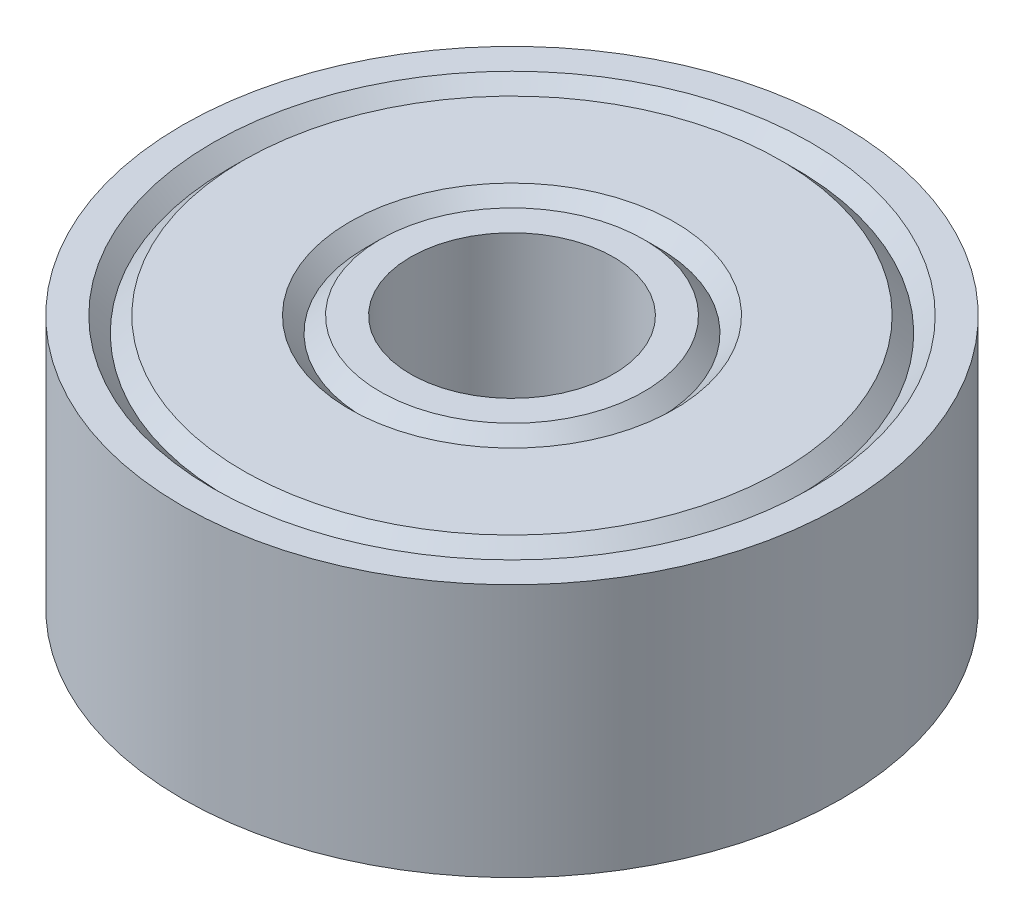
SolidWorks part; units mm, degrees
ref_plane "Front Plane" through (0, 0, 0) normal (0, 0, 1) x (1, 0, 0)
ref_plane "Top Plane" through (0, 0, 0) normal (0, 1, 0) x (1, 0, 0)
ref_plane "Right Plane" through (0, 0, 0) normal (1, 0, 0) x (0, 0, -1)
sketch "Sketch1" plane through (0, 0, 0) normal (0, 0, 1) x (1, 0, 0)
  line L0 (0, 2.5) -> (0, -2.5) construction
  line L1 (-2, 2.5) -> (-2.6, 2.5)
  line L2 (-2, 2.5) -> (-2, -2.5)
  line L3 (-2, -2.5) -> (-2.6, -2.5)
  line L4 (-6.5, 2.5) -> (-6.5, -2.5)
  line L5 (-5.9, 2.5) -> (-5.6, 2.2)
  line L6 (-5.6, 2.2) -> (-5.3, 2.5)
  line L7 (-3.2, 2.5) -> (-2.9, 2.2)
  line L8 (-2.9, 2.2) -> (-2.6, 2.5)
  line L9 (-5.9, -2.5) -> (-5.6, -2.2)
  line L10 (-5.6, -2.2) -> (-5.3, -2.5)
  line L11 (-3.2, -2.5) -> (-2.9, -2.2)
  line L12 (-2.9, -2.2) -> (-2.6, -2.5)
  line L13 (-3.2, -2.5) -> (-5.3, -2.5)
  line L14 (-5.9, -2.5) -> (-6.5, -2.5)
  line L15 (-5.9, 2.5) -> (-6.5, 2.5)
  line L16 (-3.2, 2.5) -> (-5.3, 2.5)
  line L17 (-5.6, 2.2) -> (-2.9, 2.2) construction
  line L18 (-5.6, 2.2) -> (-5.6, -2.2) construction
  line L19 (-2.9, -2.2) -> (-5.6, -2.2) construction
  line L20 (-2.9, 2.2) -> (-2.9, -2.2) construction
  line L21 (-5.6, 0) -> (-4.7, 0) construction
  line L22 (-2.6, 2.5) -> (-3.2, 2.5) construction
  line L23 (-4.7, 0) -> (-3.8, 0) construction
  line L24 (-5.6, 0) -> (-6.5, 0) construction
  line L25 (-3.8, 0) -> (-2.9, 0) construction
  line L26 (-2.9, 0) -> (-2, 0) construction
  dimension "D1" = 5
  dimension "D2" = 4
  dimension "D3" = 13
revolve "Revolve1" add sketch "Sketch1" angle 360 about L0
